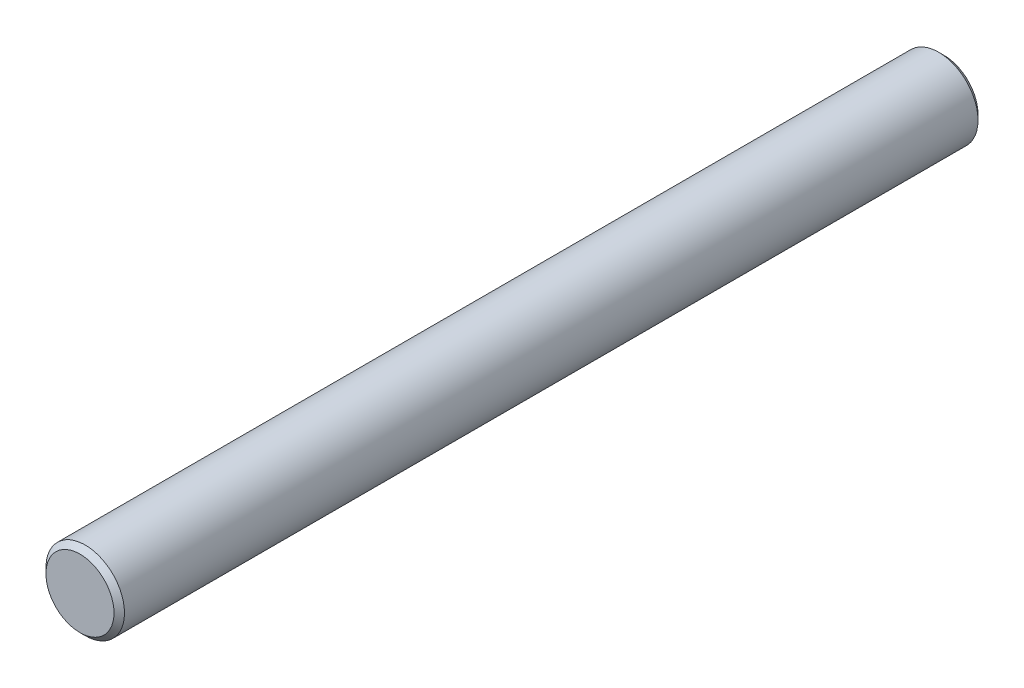
SolidWorks part; units mm, degrees
ref_plane "Front Plane" through (0, 0, 0) normal (0, 0, 1) x (1, 0, 0)
ref_plane "Top Plane" through (0, 0, 0) normal (0, 1, 0) x (1, 0, 0)
ref_plane "Right Plane" through (0, 0, 0) normal (1, 0, 0) x (0, 0, -1)
sketch "Sketch1" plane through (0, 0, 0) normal (0, 0, 1) x (1, 0, 0)
  circle A0 centre (0, 0) radius 1.5
  dimension "D1" = 3
extrude "Boss-Extrude1" add sketch "Sketch1" along normal blind 33
chamfer "Chamfer1" distance 0.2 angle 45 2 edges at (1.5, 0, 0) (1.5, 0, 33)
